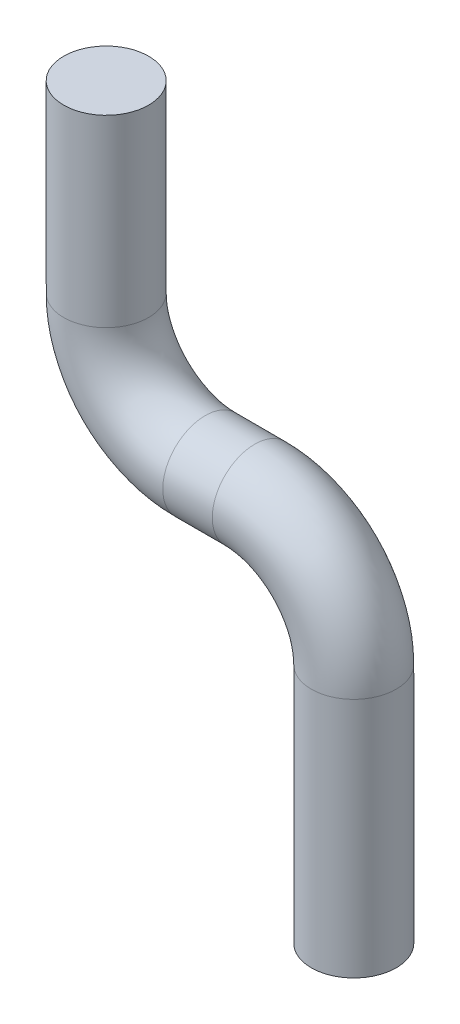
SolidWorks part; units mm, degrees
material "СТ3КП"
ref_plane "Спереди" through (0, 0, 0) normal (0, 0, 1) x (1, 0, 0)
ref_plane "Сверху" through (0, 0, 0) normal (0, 1, 0) x (1, 0, 0)
ref_plane "Справа" through (0, 0, 0) normal (1, 0, 0) x (0, 0, -1)
sketch "Эскиз1" plane through (0, 0, 0) normal (0, 1, 0) x (1, 0, 0)
  line L0 (-548.3484, 0) -> (40, 0) construction
  circle A0 centre (-6, 0) radius 6
  dimension "D1" = 12
sketch "Эскиз2" plane through (0, 0, 0) normal (0, 0, 1) x (1, 0, 0)
  line L0 (-6, 0) -> (-6, 34.1132)
  line L1 (-20, 48.1132) -> (-27, 48.1132)
  line L2 (-41, 62.1132) -> (-41, 88.1132)
  arc A0 (-27, 48.1132) -> (-41, 62.1132) centre (-27, 62.1132) cw
  arc A1 (-6, 34.1132) -> (-20, 48.1132) centre (-20, 34.1132) ccw
  point P8 (-41, 48.1132)
  point P11 (-6, 48.1132)
  dimension "D4" = 14
  dimension "D1" = 35
  dimension "D2" = 40
  dimension "D3" = 48.1132
sweep "По траектории1" add profiles "Эскиз1" path "Эскиз2"
